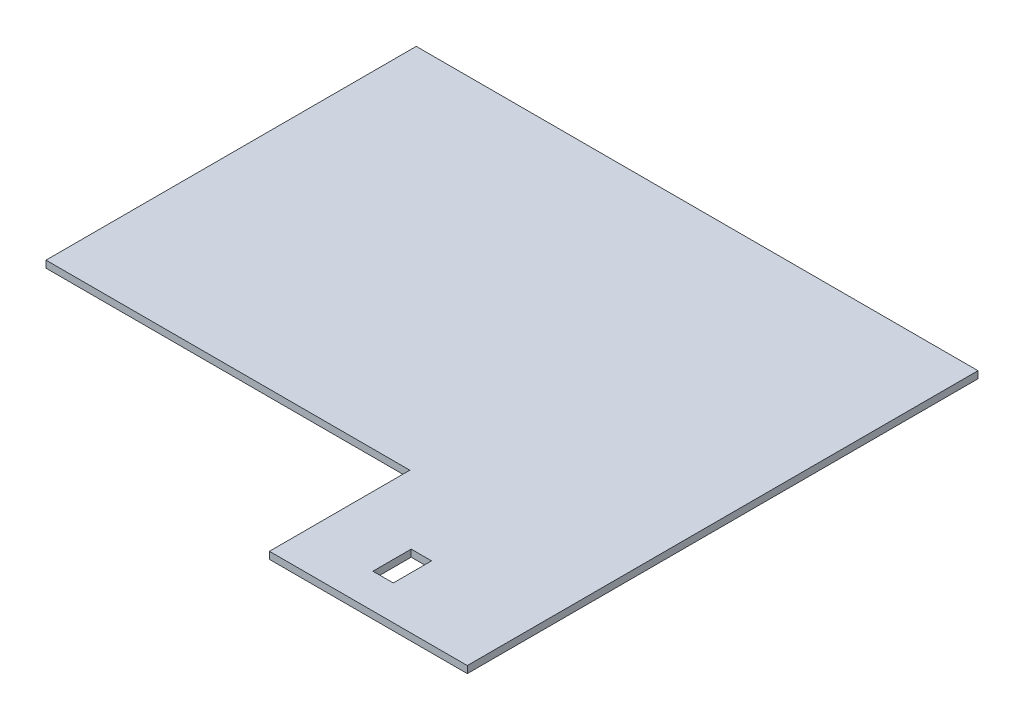
SolidWorks part; units mm, degrees
ref_plane "Alzado" through (0, 0, 0) normal (0, 0, 1) x (1, 0, 0)
ref_plane "Planta" through (0, 0, 0) normal (0, 1, 0) x (1, 0, 0)
ref_plane "Vista lateral" through (0, 0, 0) normal (1, 0, 0) x (0, 0, -1)
sketch "Croquis1" plane through (0, 0, 0) normal (0, 1, 0) x (-1, 0, 0)
  line L19 (-143.5867, 402.2958) -> (-228.5867, 402.2958)
  line L21 (-143.5867, 345.2958) -> (-143.5867, 375.2958)
  line L22 (-228.5867, 2.2958) -> (-228.5867, 402.2958)
  line L24 (211.4133, 2.2958) -> (211.4133, 292.2958)
  line L26 (-228.5867, 2.2958) -> (211.4133, 2.2958)
  line L27 (211.4133, 292.2958) -> (-73.5867, 292.2958)
  line L28 (-143.5867, 402.2958) -> (-73.5867, 402.2958)
  line L29 (-143.5867, 375.2958) -> (-143.5867, 345.2958)
  line L31 (-73.5867, 402.2958) -> (-73.5867, 292.2958)
  line L32 (-143.5867, 375.2958) -> (-127.6253, 375.2958)
  line L33 (-127.6253, 375.2958) -> (-127.6253, 345.2958)
  line L34 (-127.6253, 345.2958) -> (-143.5867, 345.2958)
  line L35 (-143.5867, 375.2958) -> (-143.5867, 345.2958)
  point P10 (0, 0)
  dimension "D1" = 400
  dimension "D2" = 440
  dimension "D3" = 85
  dimension "D4" = 290
  dimension "D5" = 70
  dimension "D7" = 30
  dimension "D8" = 27
extrude "Saliente-Extruir1" add sketch "Croquis1" along normal blind 5.5 contours L31 L28 L19 L22 L26 L24 L27 L33 L34 L21 L32
